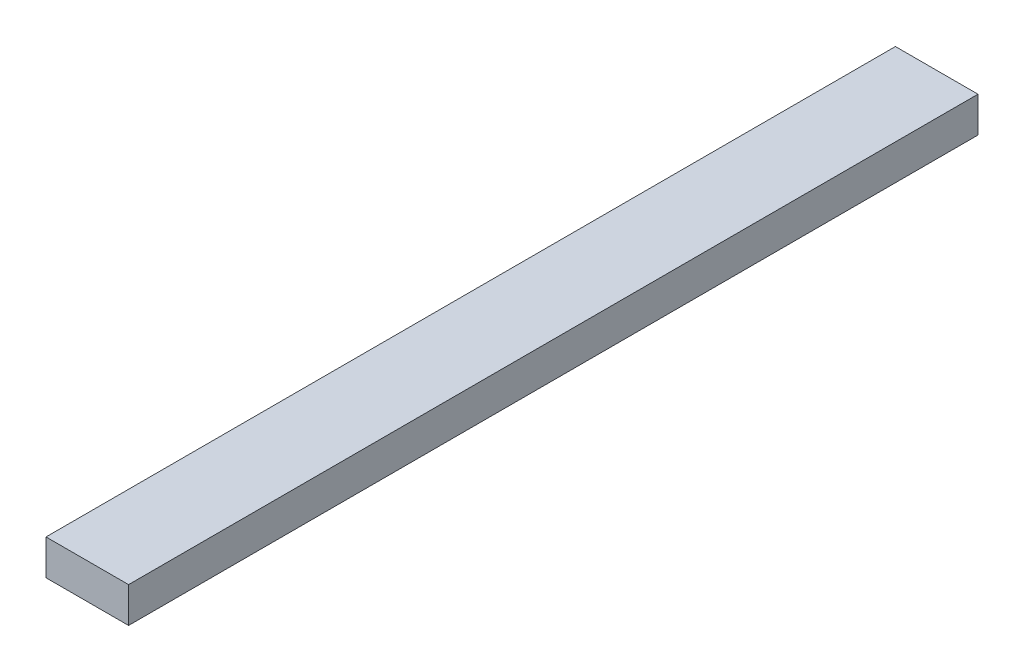
SolidWorks part; units mm, degrees
ref_plane "Front Plane" through (0, 0, 0) normal (0, 0, 1) x (1, 0, 0)
ref_plane "Top Plane" through (0, 0, 0) normal (0, 1, 0) x (1, 0, 0)
ref_plane "Right Plane" through (0, 0, 0) normal (1, 0, 0) x (0, 0, -1)
sketch "Sketch1" plane through (0, 0, 0) normal (0, 0, 1) x (1, 0, 0)
  line L1 (44.45, 19.05) -> (-44.45, 19.05)
  line L2 (44.45, 19.05) -> (44.45, -19.05)
  line L3 (44.45, -19.05) -> (-44.45, -19.05)
  line L4 (-44.45, 19.05) -> (-44.45, -19.05)
  line L5 (44.45, 19.05) -> (-44.45, -19.05) construction
  line L6 (44.45, -19.05) -> (-44.45, 19.05) construction
  point P0 (0, 0)
  dimension "D1" = 88.9
  dimension "D2" = 38.1
extrude "Boss-Extrude1" add sketch "Sketch1" along normal mid plane 914.4
equation "\"a.f\"=1.55833"
